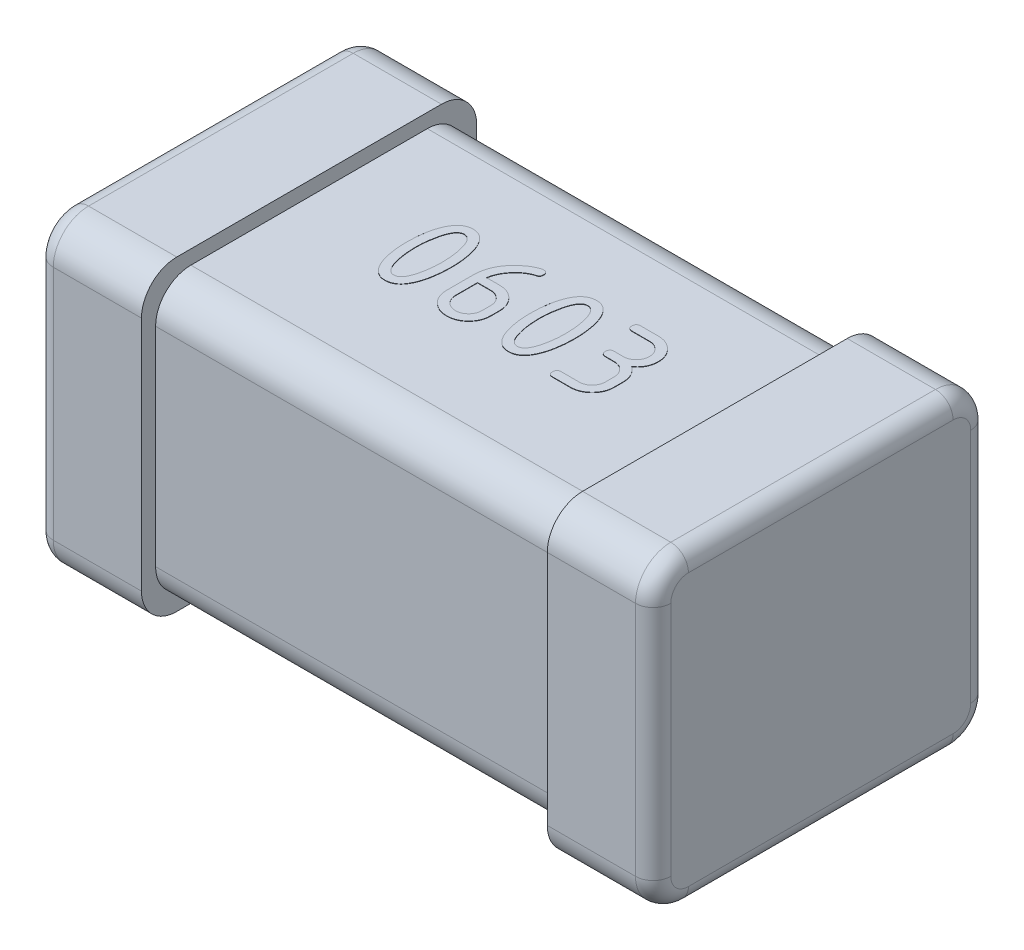
SolidWorks part; units mm, degrees
ref_plane "Front" through (0, 0, 0) normal (0, 0, 1) x (1, 0, 0)
ref_plane "Top" through (0, 0, 0) normal (0, 1, 0) x (1, 0, 0)
ref_plane "Right" through (0, 0, 0) normal (1, 0, 0) x (0, 0, -1)
sketch "Sketch1" plane through (0, 0, 0) normal (0, 1, 0) x (1, 0, 0)
  line L1 (-0.875, -0.475) -> (0.875, -0.475)
  line L2 (-0.875, -0.475) -> (-0.875, 0.475)
  line L3 (-0.875, 0.475) -> (0.875, 0.475)
  line L4 (0.875, -0.475) -> (0.875, 0.475)
  line L5 (-0.875, -0.475) -> (0.875, 0.475) construction
  line L6 (-0.875, 0.475) -> (0.875, -0.475) construction
  point P0 (0, 0)
  dimension "D1" = 0.95
  dimension "D2" = 1.75
extrude "Boss-Extrude1" add sketch "Sketch1" along normal mid plane 0.87
sketch "Sketch3" plane through (0, 0, 0) normal (1, 0, 0) x (0, 0, -1)
  line L8 (-0.435, -0.395) -> (0.435, -0.395)
  line L9 (0.435, -0.395) -> (0.435, 0.395)
  line L10 (0.435, 0.395) -> (-0.435, 0.395)
  line L11 (-0.435, 0.395) -> (-0.435, -0.395)
  line L12 (-0.435, -0.395) -> (0.435, -0.395)
  line L13 (0.435, -0.395) -> (0.435, 0.395)
  line L14 (0.435, 0.395) -> (-0.435, 0.395)
  line L15 (-0.435, 0.395) -> (-0.435, -0.395)
  dimension "D1" = 0.04
extrude "Cut-Extrude1" cut sketch "Sketch3" against normal offset from surface 0.3 and the other way offset from surface (0.575 mm away) 0.3 flip side to cut up to face at (-0.875, 0, 0) other way up to face at (0.875, 0, 0)
fillet "Fillet1" radius 0.1 4 edges at (0, -0.395, -0.435) (0, 0.395, -0.435) (0, -0.395, 0.435) (0, 0.395, 0.435)
fillet "Fillet2" radius 0.1 8 edges at (-0.725, -0.435, 0.475) (-0.725, 0.435, 0.475) (0.725, 0.435, 0.475) (0.725, -0.435, 0.475) (-0.725, -0.435, -0.475) (-0.725, 0.435, -0.475) (0.725, 0.435, -0.475) (0.725, -0.435, -0.475)
fillet "Fillet3" radius 0.05 16 edges at (0.875, 0.4057, -0.4457) (0.875, 0, -0.475) (0.875, -0.4057, -0.4457) (0.875, -0.435, 0) (0.875, -0.4057, 0.4457) (0.875, 0, 0.475) (0.875, 0.4057, 0.4457) (0.875, 0.435, 0) (-0.875, -0.4057, -0.4457) (-0.875, 0, -0.475) (-0.875, 0.4057, -0.4457) (-0.875, 0.435, 0) (-0.875, 0.4057, 0.4457) (-0.875, 0, 0.475) (-0.875, -0.4057, 0.4457) (-0.875, -0.435, 0)
sketch "Sketch4" plane through (0, 0.395, 0) normal (0, 1, 0) x (1, 0, 0)
  line L0 (-0.575, -0.0977) -> (0.575, -0.0977) construction
  line L1 (-0.575, -0.335) -> (-0.575, 0.335) construction
  line L2 (0.575, -0.375) -> (0.575, 0.375) construction
  text T0 "0603" font "@Adobe Fan Heiti Std B" height 0.25
extrude "Boss-Extrude2" add sketch "Sketch4" along normal blind 0.001
